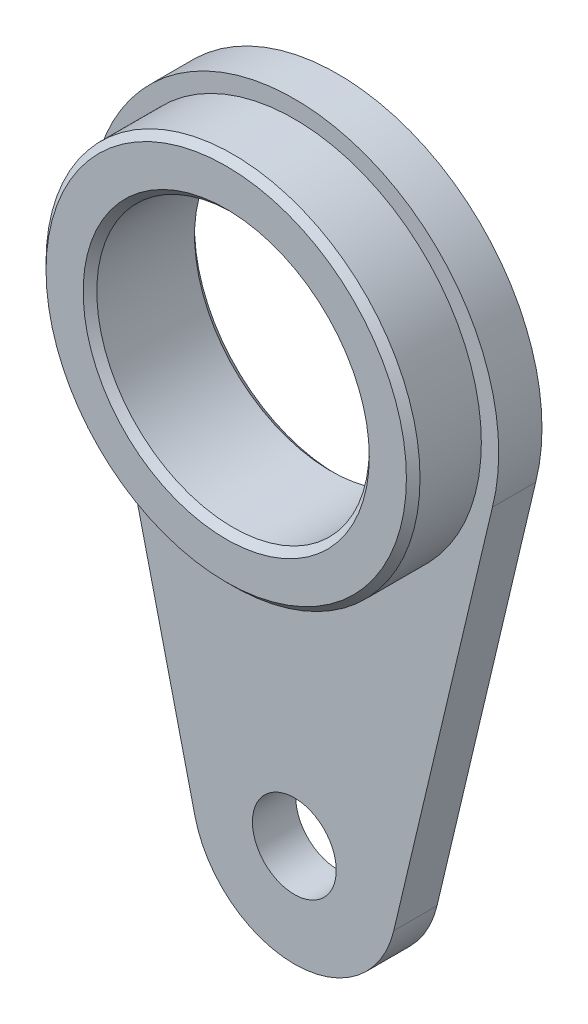
SolidWorks part; units mm, degrees
material "AISI 1010 Barra de acero laminada en caliente"
ref_plane "Alzado" through (0, 0, 0) normal (0, 0, 1) x (1, 0, 0)
ref_plane "Planta" through (0, 0, 0) normal (0, 1, 0) x (1, 0, 0)
ref_plane "Vista lateral" through (0, 0, 0) normal (1, 0, 0) x (0, 0, -1)
sketch "Croquis1" plane through (0, 0, 0) normal (0, 0, 1) x (1, 0, 0)
  line L0 (14.5953, -68.4607) -> (29.078, -7.3803)
  line L1 (-29.078, -7.3803) -> (-14.5953, -68.4607)
  arc A2 (29.078, -7.3803) -> (-29.078, -7.3803) centre (0, 0) ccw
  arc A3 (-14.5953, -68.4607) -> (14.5953, -68.4607) centre (0, -65) ccw
  circle A6 centre (0, 0) radius 25
  circle A7 centre (0, -65) radius 6.15
  dimension "D1" = 65
  dimension "D2" = 12.3
  dimension "D3" = 50
  dimension "D4" = 30
  dimension "D5" = 15
  dimension "D6" = 61.0804
extrude "Saliente-Extruir1" add sketch "Croquis1" along normal blind 6.35
sketch "Croquis2" plane through (0, 0, 6.35) normal (0, 0, 1) x (1, 0, 0)
  circle A0 centre (0, 0) radius 27.45
  circle A1 centre (0, 0) radius 20
  dimension "D1" = 54.9
  dimension "D2" = 40
extrude "Saliente-Extruir2" add sketch "Croquis2" along normal blind 10 and the other way up to surface other way up to face at (0, -31.4603, 0)
chamfer "Chaflán1" distance 1 angle 45 3 edges at (20, 0, 0) (20, 0, 16.35) (27.45, 0, 16.35)
